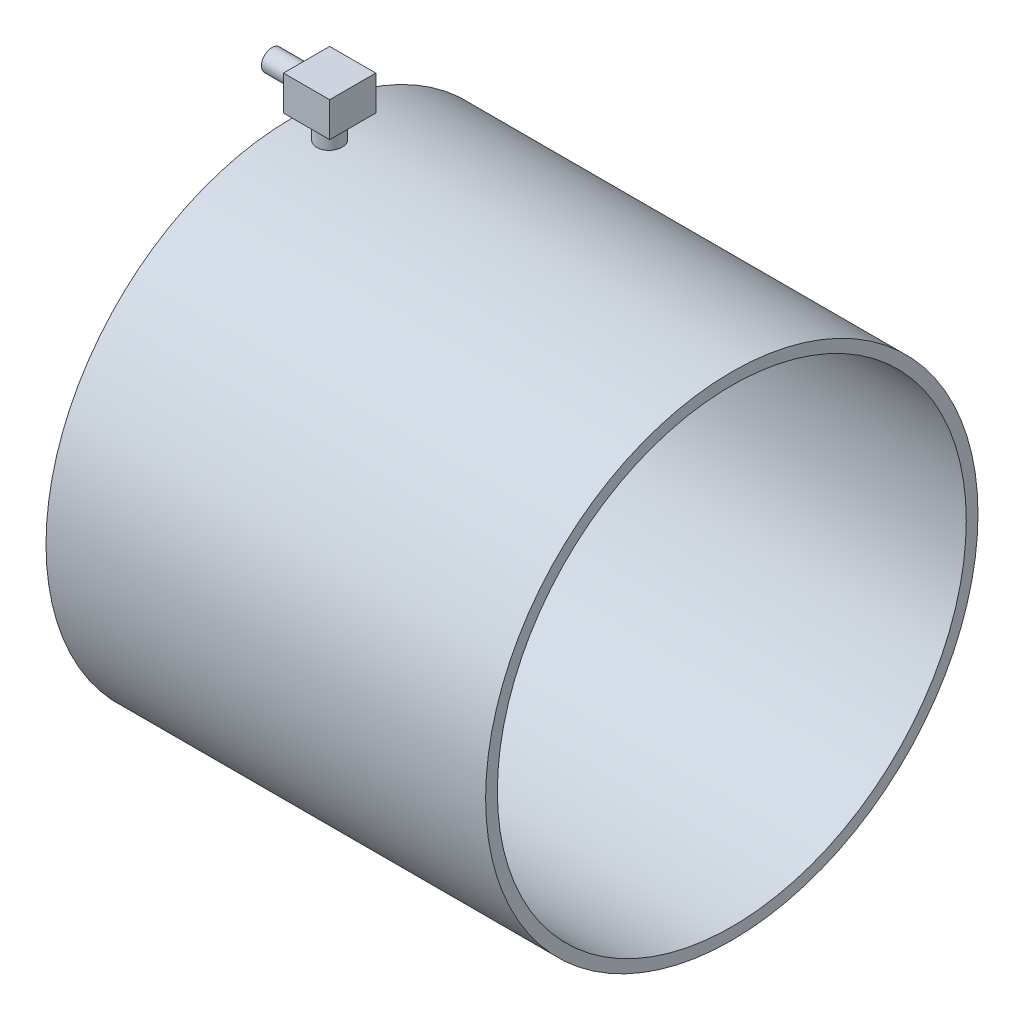
SolidWorks part; units mm, degrees
ref_plane "Front Plane" through (0, 0, 0) normal (0, 0, 1) x (1, 0, 0)
ref_plane "Top Plane" through (0, 0, 0) normal (0, 1, 0) x (1, 0, 0)
ref_plane "Right Plane" through (0, 0, 0) normal (1, 0, 0) x (0, 0, -1)
sketch "Sketch1" plane through (0, 0, 0) normal (1, 0, 0) x (0, 0, -1)
  circle A0 centre (0, 0) radius 21.336
  circle A1 centre (0, 0) radius 20.32
extrude "Boss-Extrude1" add sketch "Sketch1" along normal blind 38.1 contours A0 | A1
ref_plane "Plane1" through (0, 20.3301, 0) normal (0, 1, 0) x (1, 0, 0)
sketch "Sketch2" plane through (0, 20.3301, 0) normal (0, 1, 0) x (1, 0, 0)
  circle A0 centre (3.2449, 0) radius 1.1044
extrude "Boss-Extrude2" add sketch "Sketch2" along normal blind 3 separate body
sketch "Sketch3" plane through (0, 23.3301, 0) normal (0, 1, 0) x (1, 0, 0)
  line L1 (5.2449, 2) -> (1.2449, 2)
  line L2 (5.2449, 2) -> (5.2449, -2)
  line L3 (5.2449, -2) -> (1.2449, -2)
  line L4 (1.2449, 2) -> (1.2449, -2)
  line L5 (5.2449, 2) -> (1.2449, -2) construction
  line L6 (5.2449, -2) -> (1.2449, 2) construction
  point P0 (3.2449, 0)
  dimension "D1" = 4
  dimension "D2" = 4
extrude "Boss-Extrude3" add sketch "Sketch3" along normal blind 3
sketch "Sketch4" plane through (1.2449, 0, 0) normal (-1, 0, 0) x (0, 0, 1)
  circle A0 centre (0, 24.8301) radius 0.9133
  circle A1 centre (0, 24.8301) radius 0.6619
extrude "Boss-Extrude4" add sketch "Sketch4" along normal blind 3
